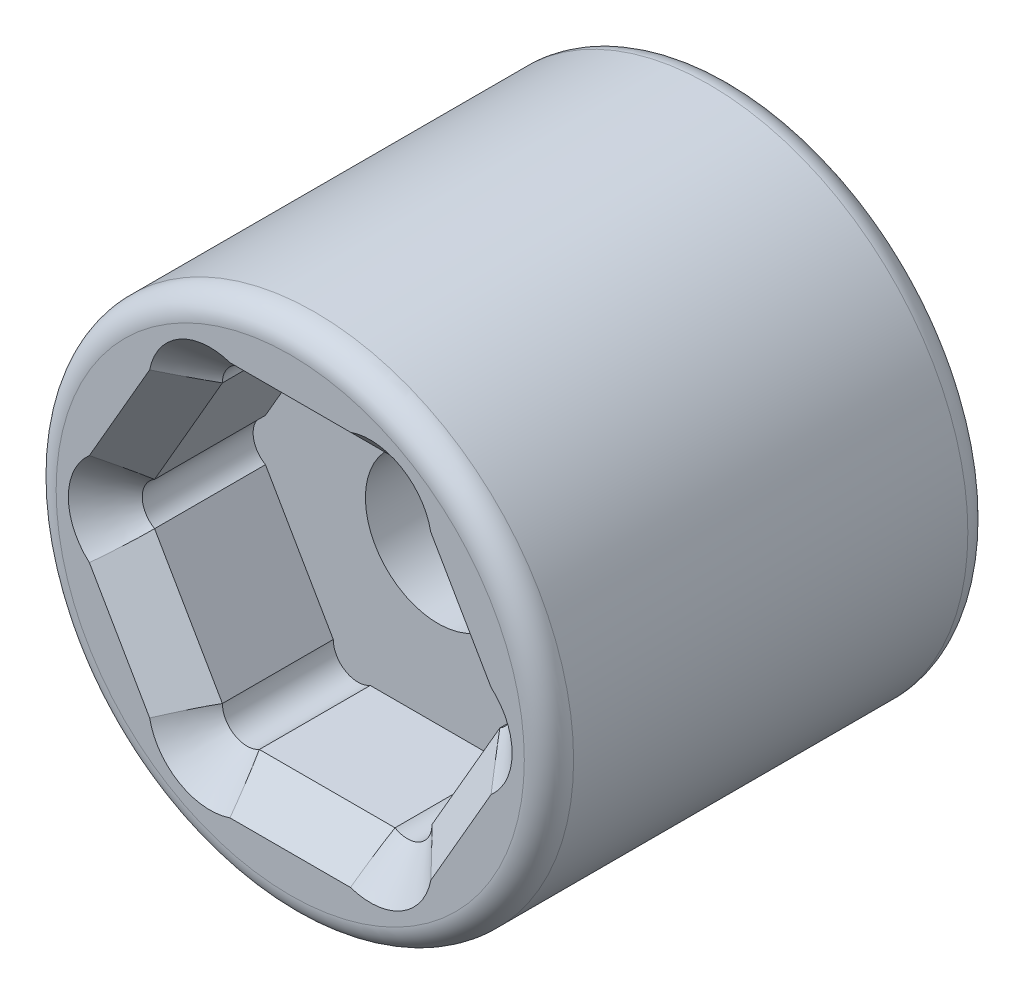
SolidWorks part; units mm, degrees
material "Nylon 101"
ref_plane "Front Plane" through (0, 0, 0) normal (0, 0, 1) x (1, 0, 0)
ref_plane "Top Plane" through (0, 0, 0) normal (0, 1, 0) x (1, 0, 0)
ref_plane "Right Plane" through (0, 0, 0) normal (1, 0, 0) x (0, 0, -1)
sketch "Sketch1" plane through (0, 0, 0) normal (0, 0, 1) x (1, 0, 0)
  line L0 (0, 0) -> (-3.7528, 6.5) construction
  line L1 (7.5056, 0) -> (3.7528, 6.5) construction
  line L2 (3.7528, 6.5) -> (-3.7528, 6.5) construction
  line L3 (-3.7528, 6.5) -> (-7.5056, 0) construction
  line L4 (-7.5056, 0) -> (-3.7528, -6.5) construction
  line L5 (-3.7528, -6.5) -> (3.7528, -6.5) construction
  line L6 (3.7528, -6.5) -> (7.5056, 0) construction
  line L7 (-2.7528, 6.5) -> (2.7528, 6.5)
  line L8 (4.2528, 5.634) -> (7.0056, 0.866)
  line L9 (7.0056, -0.866) -> (4.2528, -5.634)
  line L10 (2.7528, -6.5) -> (-2.7528, -6.5)
  line L11 (-4.2528, -5.634) -> (-7.0056, -0.866)
  line L12 (-7.0056, 0.866) -> (-4.2528, 5.634)
  circle A0 centre (0, 0) radius 6.5 construction
  arc A1 (-4.2528, 5.634) -> (-2.7528, 6.5) centre (-3.2528, 5.634) cw
  arc A2 (2.7528, 6.5) -> (4.2528, 5.634) centre (3.2528, 5.634) cw
  arc A3 (7.0056, 0.866) -> (7.0056, -0.866) centre (6.5056, 0) cw
  arc A4 (4.2528, -5.634) -> (2.7528, -6.5) centre (3.2528, -5.634) cw
  arc A5 (-2.7528, -6.5) -> (-4.2528, -5.634) centre (-3.2528, -5.634) cw
  arc A6 (-7.0056, -0.866) -> (-7.0056, 0.866) centre (-6.5056, 0) cw
  circle A7 centre (0, 0) radius 10.5
  point P29 (0, 0)
  dimension "D1" = 13
  dimension "D2" = 1
  dimension "D4" = 21
  dimension "D3" = 6
extrude "Boss-Extrude1" add sketch "Sketch1" along normal blind 6
sketch "Sketch2" plane through (0, 0, 0) normal (0, 0, -1) x (-1, 0, 0)
  circle A0 centre (0, 0) radius 2.95
  circle A1 centre (0, 0) radius 10.5
  circle A2 centre (0, 0) radius 10.5 construction
  dimension "D1" = 5.9
extrude "Boss-Extrude2" add sketch "Sketch2" along normal blind 12
chamfer "Chamfer1" distance 1.5 angle 45 13 edges at (3.7528, 6.5, 6) (5.6292, 3.25, 6) (7.5056, 0, 6) (5.6292, -3.25, 6) (3.7528, -6.5, 6) (0, -6.5, 6) (-3.7528, -6.5, 6) (-5.6292, -3.25, 6) (-7.5056, 0, 6) (-5.6292, 3.25, 6) (-3.7528, 6.5, 6) (0, 6.5, 6) (-2.95, 0, -12)
fillet "Fillet1" radius 1 2 edges at (10.5, 0, 6) (-10.5, 0, -12)
